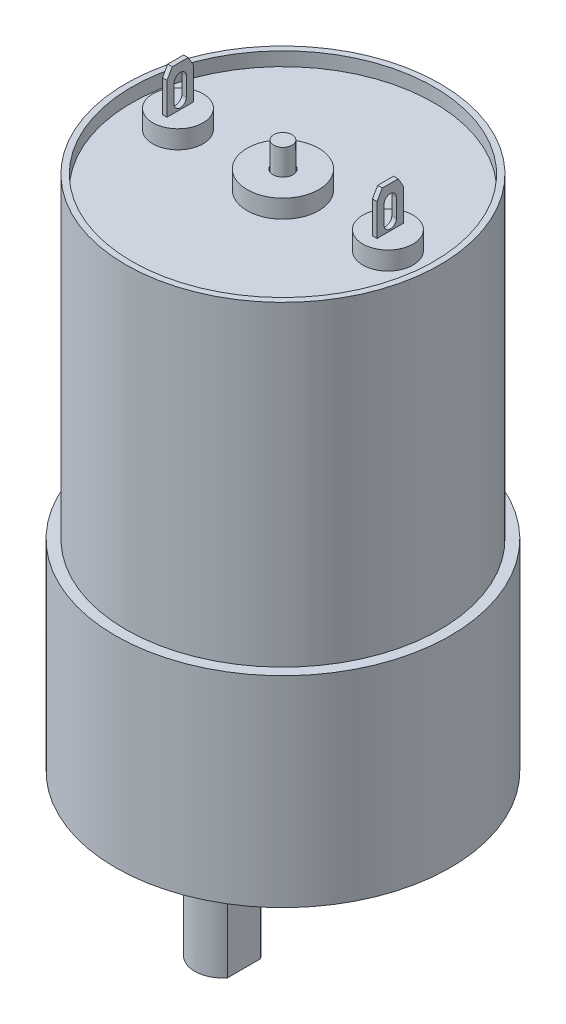
SolidWorks part; units mm, degrees
ref_plane "Front Plane" through (0, 0, 0) normal (0, 0, 1) x (1, 0, 0)
ref_plane "Top Plane" through (0, 0, 0) normal (0, 1, 0) x (1, 0, 0)
ref_plane "Right Plane" through (0, 0, 0) normal (1, 0, 0) x (0, 0, -1)
sketch "Schizzo1" plane through (0, 0, 0) normal (0, 1, 0) x (1, 0, 0)
  circle A0 centre (0, 0) radius 18.35
  dimension "D1" = 36.7
extrude "Estrusione-Estrusione1" add sketch "Schizzo1" along normal blind 22
sketch "Schizzo2" plane through (0, 22, 0) normal (0, 1, 0) x (1, 0, 0)
  circle A0 centre (0, 0) radius 17.2
  dimension "D1" = 34.4
extrude "Estrusione-Estrusione2" add sketch "Schizzo2" along normal blind 34.6
sketch "Schizzo3" plane through (0, 56.6, 0) normal (0, 1, 0) x (1, 0, 0)
  circle A0 centre (0, 0) radius 17.2 construction
  circle A1 centre (0, 0) radius 17.2
  circle A2 centre (0, 0) radius 16.55
  dimension "D1" = 0.65
extrude "Taglio-Estrusione1" cut sketch "Schizzo3" against normal blind 1.5 contours A2
sketch "Schizzo4" plane through (0, 55.1, 0) normal (0, 1, 0) x (1, 0, 0)
  line L0 (-11.5, 0) -> (11.5, 0) construction
  circle A0 centre (11.5, 0) radius 2.75
  circle A1 centre (-11.5, 0) radius 2.75
  circle A2 centre (0, 0) radius 3.925
  point P4 (0, 0)
  dimension "D2" = 5.5
  dimension "D3" = 7.85
  dimension "D1" = 23
extrude "Estrusione-Estrusione3" add sketch "Schizzo4" along normal blind 2
sketch "Schizzo5" plane through (0, 57.1, 0) normal (0, 1, 0) x (1, 0, 0)
  line L1 (-11.75, -1.45) -> (-11.25, -1.45)
  line L2 (-11.75, -1.45) -> (-11.75, 1.45)
  line L3 (-11.75, 1.45) -> (-11.25, 1.45)
  line L4 (-11.25, -1.45) -> (-11.25, 1.45)
  line L5 (-11.75, -1.45) -> (-11.25, 1.45) construction
  line L6 (-11.75, 1.45) -> (-11.25, -1.45) construction
  line L7 (11.25, -1.45) -> (11.75, -1.45)
  line L8 (11.25, -1.45) -> (11.25, 1.45)
  line L9 (11.25, 1.45) -> (11.75, 1.45)
  line L10 (11.75, -1.45) -> (11.75, 1.45)
  line L11 (11.25, -1.45) -> (11.75, 1.45) construction
  line L12 (11.25, 1.45) -> (11.75, -1.45) construction
  circle A1 centre (11.5, 0) radius 2.75
  circle A2 centre (11.5, 0) radius 2.75 construction
  circle A3 centre (-11.5, 0) radius 2.75
  circle A4 centre (-11.5, 0) radius 2.75 construction
  dimension "D3" = 0.5
  dimension "D4" = 0.5
  dimension "D5" = 2.9
  dimension "D1" = 0
  dimension "D2" = 0
extrude "Estrusione-Estrusione4" add sketch "Schizzo5" along normal blind 4.5
chamfer "Smusso1" distance 1 angle 30 4 edges at (11.5, 61.6, 1.45) (11.5, 61.6, -1.45) (-11.5, 61.6, -1.45) (-11.5, 61.6, 1.45)
sketch "Schizzo6" plane through (-11.75, 0, 0) normal (-1, 0, 0) x (0, 0, 1)
  line L0 (0, 59.95) -> (0, 57.95) construction
  line L1 (0.675, 59.95) -> (0.675, 57.95)
  line L2 (-0.675, 59.95) -> (-0.675, 57.95)
  line L5 (-1.45, 57.1) -> (1.45, 57.1) construction
  arc A0 (0.675, 59.95) -> (-0.675, 59.95) centre (0, 59.95) ccw
  arc A1 (-0.675, 57.95) -> (0.675, 57.95) centre (0, 57.95) ccw
  point P3 (0, 58.95)
  dimension "D2" = 0.85
  dimension "D3" = 1.35
  dimension "D1" = 2
extrude "Taglio-Estrusione2" cut sketch "Schizzo6" against normal through all
sketch "Schizzo7" plane through (0, 57.1, 0) normal (0, 1, 0) x (1, 0, 0)
  circle A0 centre (0, 0) radius 1.1
  dimension "D1" = 2.2
extrude "Taglio-Estrusione3" cut sketch "Schizzo7" against normal up to surface (2 mm away) up to face at (0, 55.1, 3.925)
sketch "Schizzo8" plane through (0, 55.1, 0) normal (0, 1, 0) x (1, 0, 0)
  circle A0 centre (0, 0) radius 1
  dimension "D1" = 2
extrude "Estrusione-Estrusione5" add sketch "Schizzo8" along normal blind 4.75
sketch "Schizzo9" plane through (0, 0, 0) normal (0, -1, 0) x (1, 0, 0)
  circle A0 centre (0, 0) radius 15.5 construction
  circle A1 centre (0, -15.5) radius 1.5
  circle A2 centre (-13.4234, -7.75) radius 1.5
  circle A3 centre (-13.4234, 7.75) radius 1.5
  circle A4 centre (0, 15.5) radius 1.5
  circle A5 centre (13.4234, 7.75) radius 1.5
  circle A6 centre (13.4234, -7.75) radius 1.5
  dimension "D1" = 31
  dimension "D2" = 3
  dimension "D3" = 6
extrude "Taglio-Estrusione4" cut sketch "Schizzo9" against normal blind 5
sketch "Schizzo10" plane through (0, 0, 0) normal (0, -1, 0) x (1, 0, 0)
  line L0 (-12.65, 0) -> (18.35, 0) construction
  circle A1 centre (-6.65, 0) radius 6
  circle A2 centre (0, 0) radius 18.35 construction
  dimension "D1" = 12
  dimension "D2" = 31
extrude "Estrusione-Estrusione6" add sketch "Schizzo10" along normal blind 5.85
sketch "Schizzo11" plane through (0, -5.85, 0) normal (0, -1, 0) x (1, 0, 0)
  circle A0 centre (-6.65, 0) radius 3
  dimension "D1" = 6
extrude "Estrusione-Estrusione7" add sketch "Schizzo11" along normal blind 3
sketch "Schizzo12" plane through (0, -8.85, 0) normal (0, -1, 0) x (1, 0, 0)
  line L0 (-4.25, -1.8) -> (-4.25, 1.8)
  line L1 (-4.25, 0) -> (-9.65, 0) construction
  circle A1 centre (-6.65, 0) radius 3
  circle A2 centre (-6.65, 0) radius 3
  circle M4 centre (-6.65, 0) radius 3
  dimension "D2" = 5.4
  dimension "D1" = 0
extrude "Estrusione-Estrusione8" add sketch "Schizzo12" along normal blind 12 contours L0 L1 A2 | L1 L0 M4
